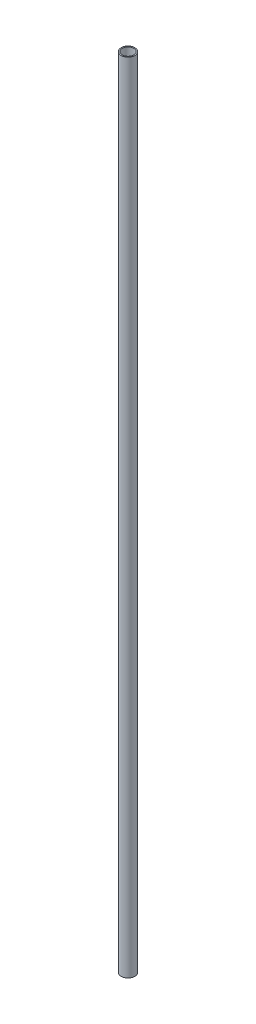
SolidWorks part; units mm, degrees
ref_plane "Front Plane" through (0, 0, 0) normal (0, 0, 1) x (1, 0, 0)
ref_plane "Top Plane" through (0, 0, 0) normal (0, 1, 0) x (1, 0, 0)
ref_plane "Right Plane" through (0, 0, 0) normal (1, 0, 0) x (0, 0, -1)
sketch "Sketch1" plane through (0, 0, 0) normal (0, 1, 0) x (1, 0, 0)
  circle A0 centre (0, 0) radius 6.35
  circle A1 centre (0, 0) radius 5.35
extrude "Boss-Extrude1" add sketch "Sketch1" along normal blind 740
